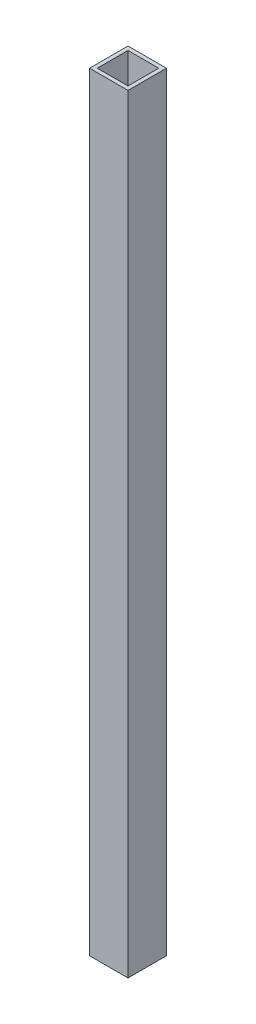
SolidWorks part; units mm, degrees
ref_plane "Front Plane" through (0, 0, 0) normal (0, 0, 1) x (1, 0, 0)
ref_plane "Top Plane" through (0, 0, 0) normal (0, 1, 0) x (1, 0, 0)
ref_plane "Right Plane" through (0, 0, 0) normal (1, 0, 0) x (0, 0, -1)
sketch "Sketch1" plane through (0, 0, 0) normal (0, 1, 0) x (1, 0, 0)
  line L0 (-8, 8) -> (8, 8)
  line L1 (-10, -10) -> (10, -10)
  line L2 (-10, -10) -> (-10, 10)
  line L3 (-10, 10) -> (10, 10)
  line L4 (10, -10) -> (10, 10)
  line L5 (-10, -10) -> (10, 10) construction
  line L6 (-10, 10) -> (10, -10) construction
  line L7 (8, -8) -> (8, 8)
  line L8 (-8, -8) -> (8, -8)
  line L9 (-8, -8) -> (-8, 8)
  point P0 (0, 0)
  dimension "D1" = 20
  dimension "D2" = 2
extrude "Boss-Extrude1" add sketch "Sketch1" along normal blind 400
